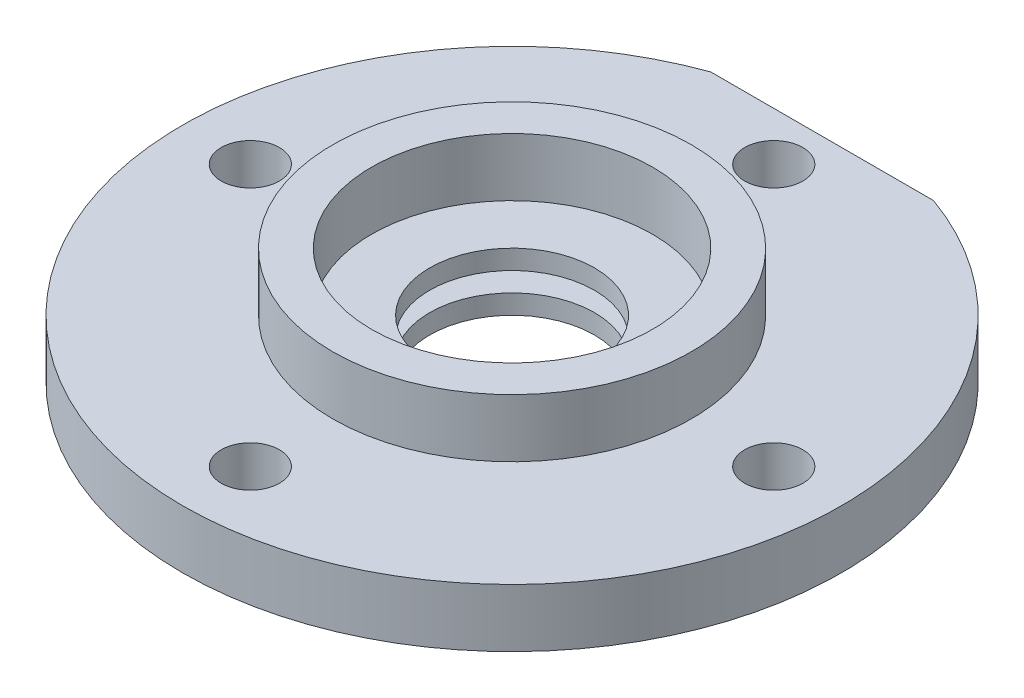
SolidWorks part; units mm, degrees
ref_plane "前视基准面" through (0, 0, 0) normal (0, 0, 1) x (1, 0, 0)
ref_plane "上视基准面" through (0, 0, 0) normal (0, 1, 0) x (1, 0, 0)
ref_plane "右视基准面" through (0, 0, 0) normal (1, 0, 0) x (0, 0, -1)
other "Configuration Table"
sketch "草图1" plane through (0, 0, 0) normal (0, 1, 0) x (1, 0, 0)
  line L0 (-11.4891, 32) -> (11.4891, 32)
  arc A0 (-11.4891, 32) -> (11.4891, 32) centre (0, 0) ccw
  circle A1 centre (0, 0) radius 27 construction
  circle A2 centre (0, 27) radius 3
  circle A3 centre (27, 0) radius 3
  circle A4 centre (0, -27) radius 3
  circle A5 centre (-27, 0) radius 3
  point P15 (0, 0)
  dimension "D1" = 68
  dimension "D2" = 54
  dimension "D3" = 6
  dimension "D5" = 32
  dimension "D4" = 4
extrude "凸台-拉伸1" add sketch "草图1" along normal blind 6
sketch "草图2" plane through (0, 6, 0) normal (0, 1, 0) x (1, 0, 0)
  circle A0 centre (0, 0) radius 18.5
  dimension "D1" = 37
extrude "凸台-拉伸2" add sketch "草图2" along normal blind 6
sketch "草图3" plane through (0, 0, 0) normal (0, 0, 1) x (1, 0, 0)
  line L0 (0, 0) -> (0, 12) construction
  line L1 (18.5, 12) -> (-18.5, 12) construction
  line L2 (0, 12) -> (14.5, 12)
  line L3 (14.5, 12) -> (14.5, 6)
  line L4 (14.5, 6) -> (8.5, 6)
  line L5 (8.5, 6) -> (8.5, 4)
  line L6 (8.5, 4) -> (12.5, 4)
  line L7 (12.5, 4) -> (12.5, 2)
  line L8 (12.5, 2) -> (8.5, 2)
  line L9 (8.5, 2) -> (8.5, 0)
  line L10 (-34, 0) -> (34, 0) construction
  line L11 (8.5, 0) -> (0, 0)
  line L12 (0, 0) -> (0, 12)
  dimension "D1" = 29
  dimension "D2" = 25
  dimension "D3" = 6
  dimension "D4" = 2
  dimension "D5" = 2
  dimension "D6" = 17
revolve "切除-旋转1" cut sketch "草图3" angle 360 about L0
